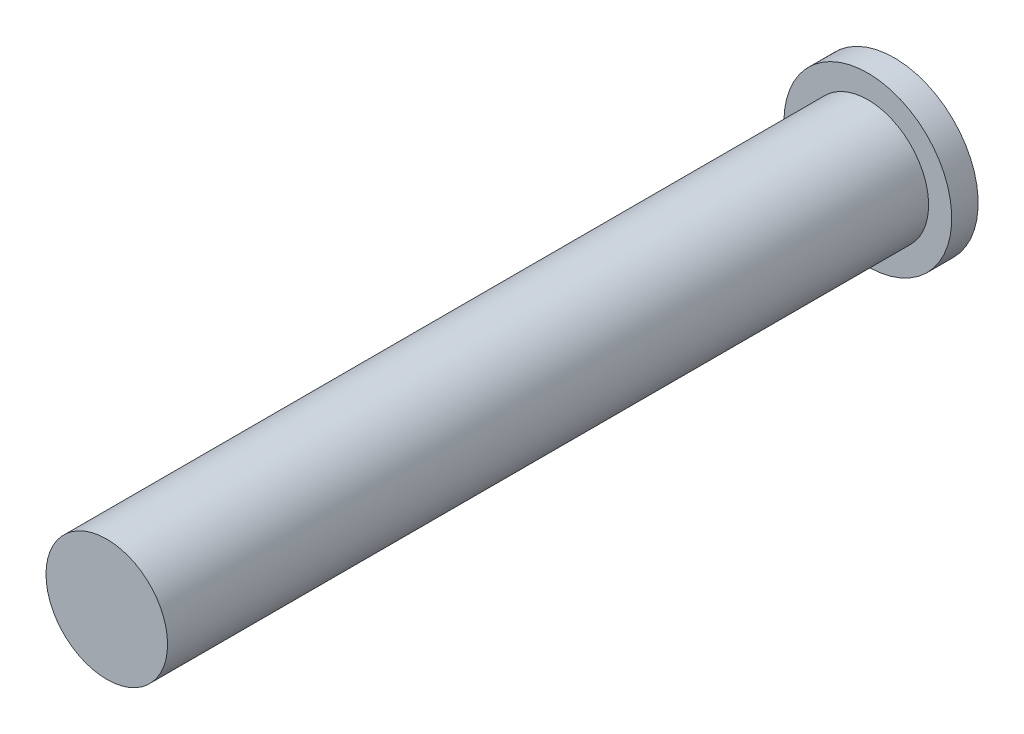
SolidWorks part; units mm, degrees
ref_plane "Alzado" through (0, 0, 0) normal (0, 0, 1) x (1, 0, 0)
ref_plane "Planta" through (0, 0, 0) normal (0, 1, 0) x (1, 0, 0)
ref_plane "Vista lateral" through (0, 0, 0) normal (1, 0, 0) x (0, 0, -1)
sketch "Croquis1" plane through (0, 0, 0) normal (0, 0, 1) x (1, 0, 0)
  circle A0 centre (0, 0) radius 11.5
  dimension "D1" = 23
extrude "Saliente-Extruir1" add sketch "Croquis1" along normal mid plane 144
sketch "Croquis2" plane through (0, 0, -72) normal (0, 0, -1) x (-1, 0, 0)
  circle A0 centre (0, 0) radius 15.875
  dimension "D1" = 31.75
extrude "Saliente-Extruir2" add sketch "Croquis2" along normal blind 5
